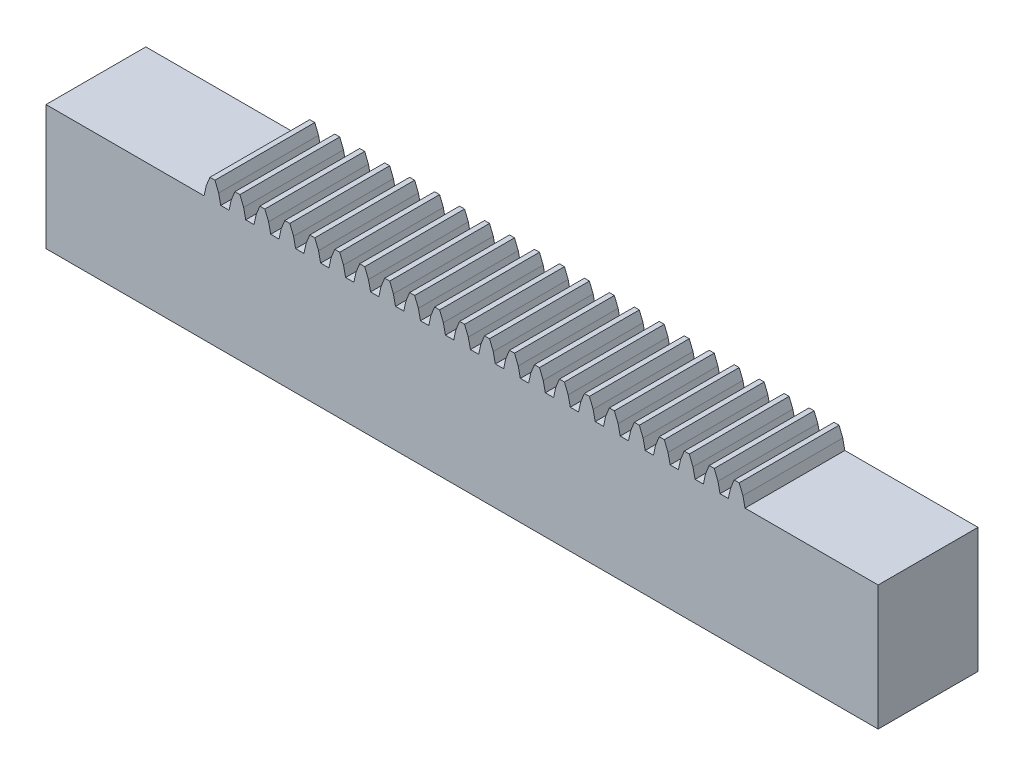
SolidWorks part; units mm, degrees
ref_plane "Front Plane" through (0, 0, 0) normal (0, 0, 1) x (1, 0, 0)
ref_plane "Top Plane" through (0, 0, 0) normal (0, 1, 0) x (1, 0, 0)
ref_plane "Right Plane" through (0, 0, 0) normal (1, 0, 0) x (0, 0, -1)
sketch "Sketch1" plane through (0, 0, 0) normal (0, 0, 1) x (1, 0, 0)
  line L0 (1.0015, 7.5) -> (0.7493, 8.6697)
  line L1 (-50, -7.5) -> (50, -7.5)
  line L2 (-50, -7.5) -> (-50, 7.5)
  line L4 (50, -7.5) -> (50, 7.5)
  line L5 (-50, -7.5) -> (50, 7.5) construction
  line L6 (-50, 7.5) -> (50, -7.5) construction
  line L7 (0.7493, 8.6697) -> (0.3016, 9.7794)
  line L8 (0.3016, 9.7794) -> (-0.3016, 9.7794)
  line L9 (-0.3016, 9.7794) -> (-0.7493, 8.6697)
  line L10 (-0.7493, 8.6697) -> (-1.0015, 7.5)
  line L12 (4.0015, 7.5) -> (3.7493, 8.6697)
  line L13 (3.7493, 8.6697) -> (3.3016, 9.7794)
  line L14 (3.3016, 9.7794) -> (2.6984, 9.7794)
  line L15 (2.6984, 9.7794) -> (2.2507, 8.6697)
  line L16 (2.2507, 8.6697) -> (1.9985, 7.5)
  line L18 (7.0015, 7.5) -> (6.7493, 8.6697)
  line L19 (6.7493, 8.6697) -> (6.3016, 9.7794)
  line L20 (6.3016, 9.7794) -> (5.6984, 9.7794)
  line L21 (5.6984, 9.7794) -> (5.2507, 8.6697)
  line L22 (5.2507, 8.6697) -> (4.9985, 7.5)
  line L24 (10.0015, 7.5) -> (9.7493, 8.6697)
  line L25 (9.7493, 8.6697) -> (9.3016, 9.7794)
  line L26 (9.3016, 9.7794) -> (8.6984, 9.7794)
  line L27 (8.6984, 9.7794) -> (8.2507, 8.6697)
  line L28 (8.2507, 8.6697) -> (7.9985, 7.5)
  line L30 (13.0015, 7.5) -> (12.7493, 8.6697)
  line L31 (12.7493, 8.6697) -> (12.3016, 9.7794)
  line L32 (12.3016, 9.7794) -> (11.6984, 9.7794)
  line L33 (11.6984, 9.7794) -> (11.2507, 8.6697)
  line L34 (11.2507, 8.6697) -> (10.9985, 7.5)
  line L36 (16.0015, 7.5) -> (15.7493, 8.6697)
  line L37 (15.7493, 8.6697) -> (15.3016, 9.7794)
  line L38 (15.3016, 9.7794) -> (14.6984, 9.7794)
  line L39 (14.6984, 9.7794) -> (14.2507, 8.6697)
  line L40 (14.2507, 8.6697) -> (13.9985, 7.5)
  line L42 (19.0015, 7.5) -> (18.7493, 8.6697)
  line L43 (18.7493, 8.6697) -> (18.3016, 9.7794)
  line L44 (18.3016, 9.7794) -> (17.6984, 9.7794)
  line L45 (17.6984, 9.7794) -> (17.2507, 8.6697)
  line L46 (17.2507, 8.6697) -> (16.9985, 7.5)
  line L48 (22.0015, 7.5) -> (21.7493, 8.6697)
  line L49 (21.7493, 8.6697) -> (21.3016, 9.7794)
  line L50 (21.3016, 9.7794) -> (20.6984, 9.7794)
  line L51 (20.6984, 9.7794) -> (20.2507, 8.6697)
  line L52 (20.2507, 8.6697) -> (19.9985, 7.5)
  line L54 (25.0015, 7.5) -> (24.7493, 8.6697)
  line L55 (24.7493, 8.6697) -> (24.3016, 9.7794)
  line L56 (24.3016, 9.7794) -> (23.6984, 9.7794)
  line L57 (23.6984, 9.7794) -> (23.2507, 8.6697)
  line L58 (23.2507, 8.6697) -> (22.9985, 7.5)
  line L60 (28.0015, 7.5) -> (27.7493, 8.6697)
  line L61 (27.7493, 8.6697) -> (27.3016, 9.7794)
  line L62 (27.3016, 9.7794) -> (26.6984, 9.7794)
  line L63 (26.6984, 9.7794) -> (26.2507, 8.6697)
  line L64 (26.2507, 8.6697) -> (25.9985, 7.5)
  line L66 (31.0015, 7.5) -> (30.7493, 8.6697)
  line L67 (30.7493, 8.6697) -> (30.3016, 9.7794)
  line L68 (30.3016, 9.7794) -> (29.6984, 9.7794)
  line L69 (29.6984, 9.7794) -> (29.2507, 8.6697)
  line L70 (29.2507, 8.6697) -> (28.9985, 7.5)
  line L72 (34.0015, 7.5) -> (33.7493, 8.6697)
  line L73 (33.7493, 8.6697) -> (33.3016, 9.7794)
  line L74 (33.3016, 9.7794) -> (32.6984, 9.7794)
  line L75 (32.6984, 9.7794) -> (32.2507, 8.6697)
  line L76 (32.2507, 8.6697) -> (31.9985, 7.5)
  line L78 (1.0015, 7.5) -> (1.9985, 7.5)
  line L79 (4.0015, 7.5) -> (4.9985, 7.5)
  line L80 (7.0015, 7.5) -> (7.9985, 7.5)
  line L81 (10.0015, 7.5) -> (10.9985, 7.5)
  line L82 (13.0015, 7.5) -> (13.9985, 7.5)
  line L83 (16.0015, 7.5) -> (16.9985, 7.5)
  line L84 (19.0015, 7.5) -> (19.9985, 7.5)
  line L85 (22.0015, 7.5) -> (22.9985, 7.5)
  line L86 (25.0015, 7.5) -> (25.9985, 7.5)
  line L87 (28.0015, 7.5) -> (28.9985, 7.5)
  line L88 (31.0015, 7.5) -> (31.9985, 7.5)
  line L89 (34.0015, 7.5) -> (50, 7.5)
  line L150 (-1.0015, 7.5) -> (-1.9985, 7.5)
  line L151 (-3.7493, 8.6697) -> (-4.0015, 7.5)
  line L152 (-3.3016, 9.7794) -> (-3.7493, 8.6697)
  line L153 (-2.6984, 9.7794) -> (-3.3016, 9.7794)
  line L154 (-2.2507, 8.6697) -> (-2.6984, 9.7794)
  line L155 (-1.9985, 7.5) -> (-2.2507, 8.6697)
  line L156 (-6.7493, 8.6697) -> (-7.0015, 7.5)
  line L157 (-6.3016, 9.7794) -> (-6.7493, 8.6697)
  line L158 (-5.6984, 9.7794) -> (-6.3016, 9.7794)
  line L159 (-5.2507, 8.6697) -> (-5.6984, 9.7794)
  line L160 (-4.9985, 7.5) -> (-5.2507, 8.6697)
  line L161 (-9.7493, 8.6697) -> (-10.0015, 7.5)
  line L162 (-9.3016, 9.7794) -> (-9.7493, 8.6697)
  line L163 (-8.6984, 9.7794) -> (-9.3016, 9.7794)
  line L164 (-8.2507, 8.6697) -> (-8.6984, 9.7794)
  line L165 (-7.9985, 7.5) -> (-8.2507, 8.6697)
  line L166 (-12.7493, 8.6697) -> (-13.0015, 7.5)
  line L167 (-12.3016, 9.7794) -> (-12.7493, 8.6697)
  line L168 (-11.6984, 9.7794) -> (-12.3016, 9.7794)
  line L169 (-11.2507, 8.6697) -> (-11.6984, 9.7794)
  line L170 (-10.9985, 7.5) -> (-11.2507, 8.6697)
  line L171 (-15.7493, 8.6697) -> (-16.0015, 7.5)
  line L172 (-15.3016, 9.7794) -> (-15.7493, 8.6697)
  line L173 (-14.6984, 9.7794) -> (-15.3016, 9.7794)
  line L174 (-14.2507, 8.6697) -> (-14.6984, 9.7794)
  line L175 (-13.9985, 7.5) -> (-14.2507, 8.6697)
  line L176 (-18.7493, 8.6697) -> (-19.0015, 7.5)
  line L177 (-18.3016, 9.7794) -> (-18.7493, 8.6697)
  line L178 (-17.6984, 9.7794) -> (-18.3016, 9.7794)
  line L179 (-17.2507, 8.6697) -> (-17.6984, 9.7794)
  line L180 (-16.9985, 7.5) -> (-17.2507, 8.6697)
  line L181 (-21.7493, 8.6697) -> (-22.0015, 7.5)
  line L182 (-21.3016, 9.7794) -> (-21.7493, 8.6697)
  line L183 (-20.6984, 9.7794) -> (-21.3016, 9.7794)
  line L184 (-20.2507, 8.6697) -> (-20.6984, 9.7794)
  line L185 (-19.9985, 7.5) -> (-20.2507, 8.6697)
  line L186 (-24.7493, 8.6697) -> (-25.0015, 7.5)
  line L187 (-24.3016, 9.7794) -> (-24.7493, 8.6697)
  line L188 (-23.6984, 9.7794) -> (-24.3016, 9.7794)
  line L189 (-23.2507, 8.6697) -> (-23.6984, 9.7794)
  line L190 (-22.9985, 7.5) -> (-23.2507, 8.6697)
  line L191 (-27.7493, 8.6697) -> (-28.0015, 7.5)
  line L192 (-27.3016, 9.7794) -> (-27.7493, 8.6697)
  line L193 (-26.6984, 9.7794) -> (-27.3016, 9.7794)
  line L194 (-26.2507, 8.6697) -> (-26.6984, 9.7794)
  line L195 (-25.9985, 7.5) -> (-26.2507, 8.6697)
  line L196 (-30.7493, 8.6697) -> (-31.0015, 7.5)
  line L197 (-30.3016, 9.7794) -> (-30.7493, 8.6697)
  line L198 (-29.6984, 9.7794) -> (-30.3016, 9.7794)
  line L199 (-29.2507, 8.6697) -> (-29.6984, 9.7794)
  line L200 (-28.9985, 7.5) -> (-29.2507, 8.6697)
  line L201 (-4.0015, 7.5) -> (-4.9985, 7.5)
  line L202 (-7.0015, 7.5) -> (-7.9985, 7.5)
  line L203 (-13.0015, 7.5) -> (-13.9985, 7.5)
  line L204 (-10.0015, 7.5) -> (-10.9985, 7.5)
  line L205 (-19.0015, 7.5) -> (-19.9985, 7.5)
  line L206 (-16.0015, 7.5) -> (-16.9985, 7.5)
  line L207 (-22.0015, 7.5) -> (-22.9985, 7.5)
  line L208 (-25.0015, 7.5) -> (-25.9985, 7.5)
  line L209 (-28.0015, 7.5) -> (-28.9985, 7.5)
  line L210 (-31.0015, 7.5) -> (-50, 7.5)
  point P0 (0, 0)
  point P13 (0, 9.7794)
  dimension "D1" = 100
  dimension "D2" = 15
  dimension "D3" = 0.6033
  dimension "D4" = 1.1966
  dimension "D5" = 1.1966
  dimension "D6" = 2.0029
  dimension "D7" = 11
  dimension "D10" = 111.97
  dimension "D11" = 12
extrude "Boss-Extrude1" add sketch "Sketch1" along normal blind 12
